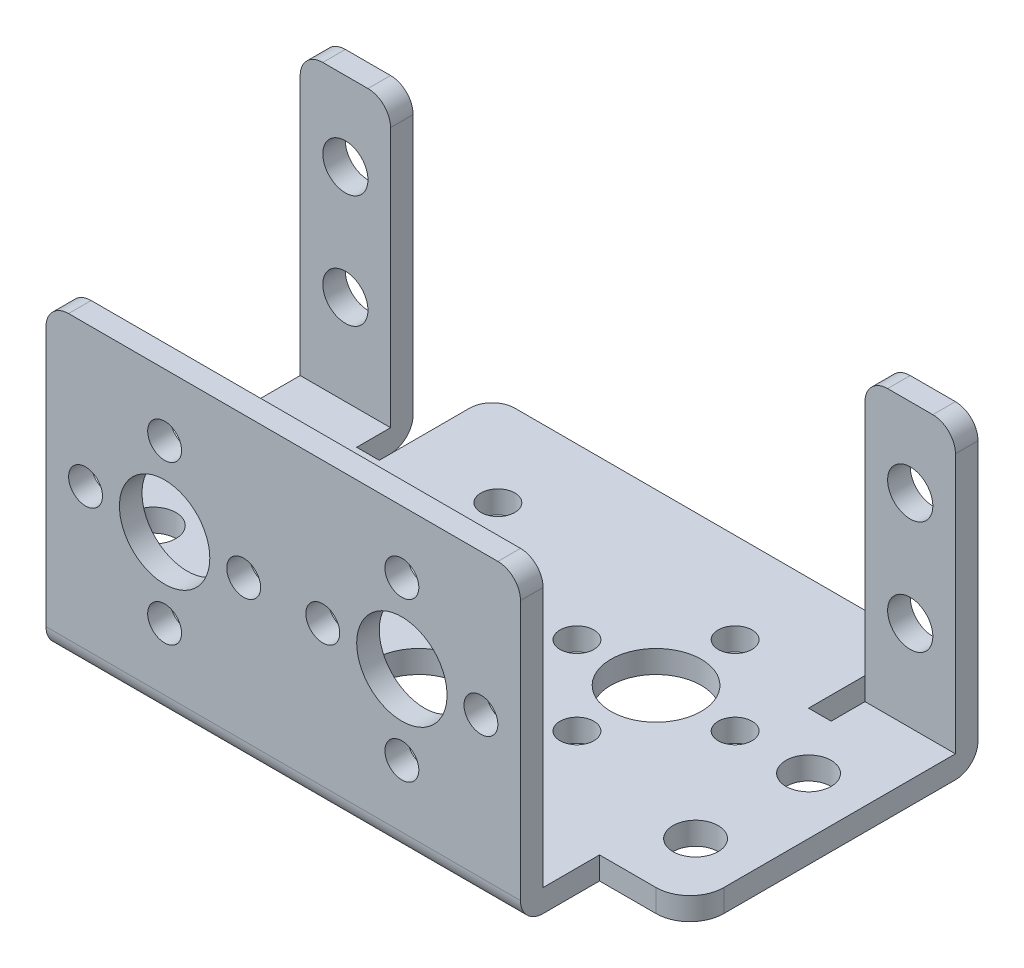
SolidWorks part; units mm, degrees
ref_plane "前视基准面" through (0, 0, 0) normal (0, 0, 1) x (1, 0, 0)
ref_plane "上视基准面" through (0, 0, 0) normal (0, 1, 0) x (1, 0, 0)
ref_plane "右视基准面" through (0, 0, 0) normal (1, 0, 0) x (0, 0, -1)
sketch "草图1" plane through (0, 0, 0) normal (0, 1, 0) x (1, 0, 0)
  line L0 (0, 0) -> (-50000, 0) construction
  line L1 (0, 0) -> (0, 50000) construction
  line L2 (-40, 2.25) -> (40, 2.25) construction
  line L3 (-17, 17.25) -> (17, 17.25)
  line L4 (-29, 12.25) -> (-29, -10.25)
  line L5 (-21, -20.25) -> (21, -20.25)
  line L6 (29, 12.25) -> (29, -10.25)
  line L7 (-40, -7.75) -> (40, -7.75) construction
  line L8 (-10.5, 22.8573) -> (-10.5, -25.8546) construction
  line L9 (10.5, 22.8573) -> (10.5, -25.8546) construction
  line L10 (-26, -13.25) -> (-21, -13.25)
  line L11 (-15, -8.25) -> (24.0767, -8.25) construction
  line L12 (-19, 15.25) -> (-19, 7.25)
  line L13 (19, 15.25) -> (19, 7.25)
  line L14 (-21, 12.25) -> (-21, 7.25)
  line L15 (21, 12.25) -> (21, 7.25)
  line L16 (-29, 12.25) -> (-21, 12.25)
  line L20 (-21, -13.25) -> (-21, -20.25)
  line L21 (21, -13.25) -> (26, -13.25)
  line L22 (21, -13.25) -> (21, -20.25)
  line L23 (-21, 7.25) -> (-19, 7.25)
  line L24 (19, 7.25) -> (21, 7.25)
  line L28 (21, 12.25) -> (29, 12.25)
  circle A0 centre (0, -8.25) radius 4
  circle A1 centre (0, -8.25) radius 7 construction
  circle A2 centre (0, -1.25) radius 1.3834
  circle A3 centre (-7, -8.25) radius 1.5
  circle A4 centre (0, -15.25) radius 1.5
  circle A5 centre (7, -8.25) radius 1.5
  circle A6 centre (-10.5, 2.25) radius 4
  circle A7 centre (-10.5, 2.25) radius 7 construction
  circle A8 centre (-10.5, 9.25) radius 1.5
  circle A9 centre (-3.5, 2.25) radius 1.5
  circle A10 centre (-17.5, 2.25) radius 1.5
  circle A11 centre (-10.5, -4.75) radius 1.5
  circle A12 centre (10.5, -4.75) radius 1.5
  circle A13 centre (3.5, 2.25) radius 1.5
  circle A14 centre (17.5, 2.25) radius 1.5
  circle A15 centre (10.5, 9.25) radius 1.5
  circle A16 centre (10.5, 2.25) radius 7 construction
  circle A17 centre (10.5, 2.25) radius 4
  circle A18 centre (-24, 2.25) radius 2
  circle A19 centre (24, 2.25) radius 2
  circle A20 centre (-24, -7.75) radius 2
  circle A21 centre (24, -7.75) radius 2
  arc A22 (26, -13.25) -> (29, -10.25) centre (26, -10.25) ccw
  arc A23 (-26, -13.25) -> (-29, -10.25) centre (-26, -10.25) cw
  arc A24 (19, 15.25) -> (17, 17.25) centre (17, 15.25) ccw
  arc A25 (-19, 15.25) -> (-17, 17.25) centre (-17, 15.25) cw
  dimension "D6" = 30.5
  dimension "D7" = 12
  dimension "D8" = 14
  dimension "D9" = 3
  dimension "D10" = 8
  dimension "D11" = 8
  dimension "D12" = 14
  dimension "D13" = 4
  dimension "D19" = 3
  dimension "D2" = 2
  dimension "D3" = 22.5
  dimension "D4" = 12.5
  dimension "D14" = 48
  dimension "D15" = 10
  dimension "D16" = 19
  dimension "D17" = 2
  dimension "D18" = 58
  dimension "D20" = 38
  dimension "D21" = 21
  dimension "D23" = 5
extrude "凸台-拉伸1" add sketch "草图1" along normal blind 2
sketch "草图2" plane through (0, 2, 0) normal (0, 1, 0) x (1, 0, 0)
  line L0 (-21, 7.25) -> (-21, 12.25) construction
  line L1 (-29, 12.25) -> (-21, 12.25)
  line L2 (-29, 12.25) -> (-29, 10.25)
  line L3 (-29, 10.25) -> (-21, 10.25)
  line L4 (-21, 12.25) -> (-21, 10.25)
  line L5 (-21, -20.25) -> (21, -20.25) construction
  line L6 (-21, -20.25) -> (21, -20.25)
  line L7 (-21, -20.25) -> (-21, -18.25)
  line L8 (-21, -18.25) -> (21, -18.25)
  line L9 (21, -20.25) -> (21, -18.25)
  line L10 (21, -20.25) -> (21, -13.25) construction
  line L12 (29, -10.25) -> (29, 12.25) construction
  line L13 (29, 10.25) -> (21, 10.25)
  line L14 (29, 10.25) -> (29, 12.25)
  line L15 (29, 12.25) -> (21, 12.25)
  line L16 (21, 10.25) -> (21, 12.25)
  line L17 (29, 12.25) -> (21, 12.25) construction
  dimension "D1" = 2
  dimension "D2" = 2
  dimension "D3" = 2
  dimension "D4" = 42
extrude "凸台-拉伸2" add sketch "草图2" along normal blind 25
fillet "圆角1" radius 2 3 edges at (25, 0, -12.25) (0, 0, 20.25) (-25, 0, -12.25)
sketch "草图3" plane through (0, 0, 20.25) normal (0, 0, 1) x (1, 0, 0)
  line L0 (-35.2091, 14.5) -> (49964.7909, 14.5) construction
  line L1 (0, 0) -> (0, 50000) construction
  line L2 (-26, 0) -> (-21, 0) construction
  line L3 (-10.5, 14.5) -> (-10.5, 50014.5) construction
  line L4 (10.5, 14.5) -> (10.5, 50014.5) construction
  line L5 (35.2091, 14.5) -> (-49964.7909, 14.5) construction
  line L7 (-19, 27) -> (19, 27)
  line L8 (-21, 28.1135) -> (21, 28.1135)
  line L9 (-21, 28.1135) -> (-21, 25)
  line L11 (21, 28.1135) -> (21, 25)
  circle A0 centre (-10.5, 14.5) radius 4
  circle A1 centre (-10.5, 14.5) radius 7 construction
  circle A2 centre (-10.5, 21.5) radius 1.5
  circle A3 centre (-17.5, 14.5) radius 1.5
  circle A4 centre (-3.5, 14.5) radius 1.5
  circle A5 centre (-10.5, 7.5) radius 1.5
  circle A6 centre (10.5, 14.5) radius 7 construction
  circle A7 centre (17.5, 14.5) radius 1.5
  circle A8 centre (10.5, 14.5) radius 4
  circle A9 centre (3.5, 14.5) radius 1.5
  circle A10 centre (10.5, 21.5) radius 1.5
  circle A11 centre (10.5, 7.5) radius 1.5
  arc A12 (21, 25) -> (19, 27) centre (19, 25) ccw
  arc A13 (-21, 25) -> (-19, 27) centre (-19, 25) cw
  point P44 (-21, 27)
  dimension "D3" = 2
  dimension "D4" = 8
  dimension "D5" = 3
  dimension "D6" = 14
  dimension "D1" = 14.5
  dimension "D2" = 10.5
extrude "切除-拉伸2" cut sketch "草图3" against normal blind 2
fillet "圆角2" radius 2 4 edges at (29, 27, -11.25) (21, 27, -11.25) (-21, 27, -11.25) (-29, 27, -11.25)
sketch "草图4" plane through (0, 0, -12.25) normal (0, 0, -1) x (-1, 0, 0)
  line L0 (-25, 31.9502) -> (-25, -3.6937) construction
  line L1 (-29, 25) -> (-29, 2) construction
  line L3 (25, -2.1538) -> (25, 31.2345) construction
  line L4 (21, 25) -> (21, 2) construction
  circle A0 centre (-25, 20) radius 2
  circle A1 centre (-25, 10) radius 2
  circle A2 centre (25, 20) radius 2
  circle A3 centre (25, 10) radius 2
  dimension "D2" = 10
  dimension "D3" = 4
  dimension "D4" = 4
  dimension "D5" = 4
  dimension "D6" = 4
  dimension "D7" = 4
  dimension "D1" = 4
extrude "切除-拉伸3" cut sketch "草图4" against normal blind 90
